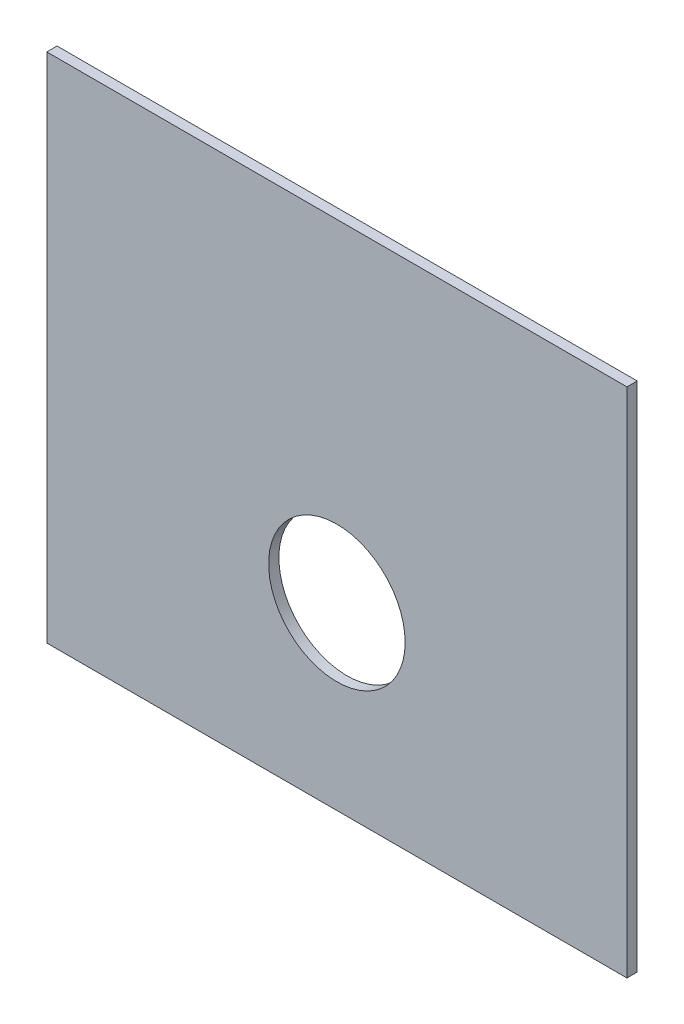
SolidWorks part; units mm, degrees
ref_plane "前基準面" through (0, 0, 0) normal (0, 0, 1) x (1, 0, 0)
ref_plane "上基準面" through (0, 0, 0) normal (0, 1, 0) x (1, 0, 0)
ref_plane "右基準面" through (0, 0, 0) normal (1, 0, 0) x (0, 0, -1)
sketch "草圖1" plane through (0, 0, 0) normal (0, 0, 1) x (1, 0, 0)
  line L1 (0, 0) -> (170, 0)
  line L2 (0, 0) -> (0, 150)
  line L3 (0, 150) -> (170, 150)
  line L4 (170, 0) -> (170, 150)
  dimension "D1" = 170
  dimension "D2" = 150
extrude "填料-伸長1" add sketch "草圖1" along normal blind 3
sketch "草圖2" plane through (0, 0, 3) normal (0, 0, 1) x (1, 0, 0)
  line L0 (85, 150) -> (85, 0) construction
  line L1 (170, 150) -> (0, 150) construction
  line L2 (0, 0) -> (170, 0) construction
  circle A0 centre (85, 52.6642) radius 20
  point P8 (85, 52.6642)
  dimension "D1" = 40
  dimension "D2" = 52.6642
extrude "除料-伸長1" cut sketch "草圖2" against normal through all
